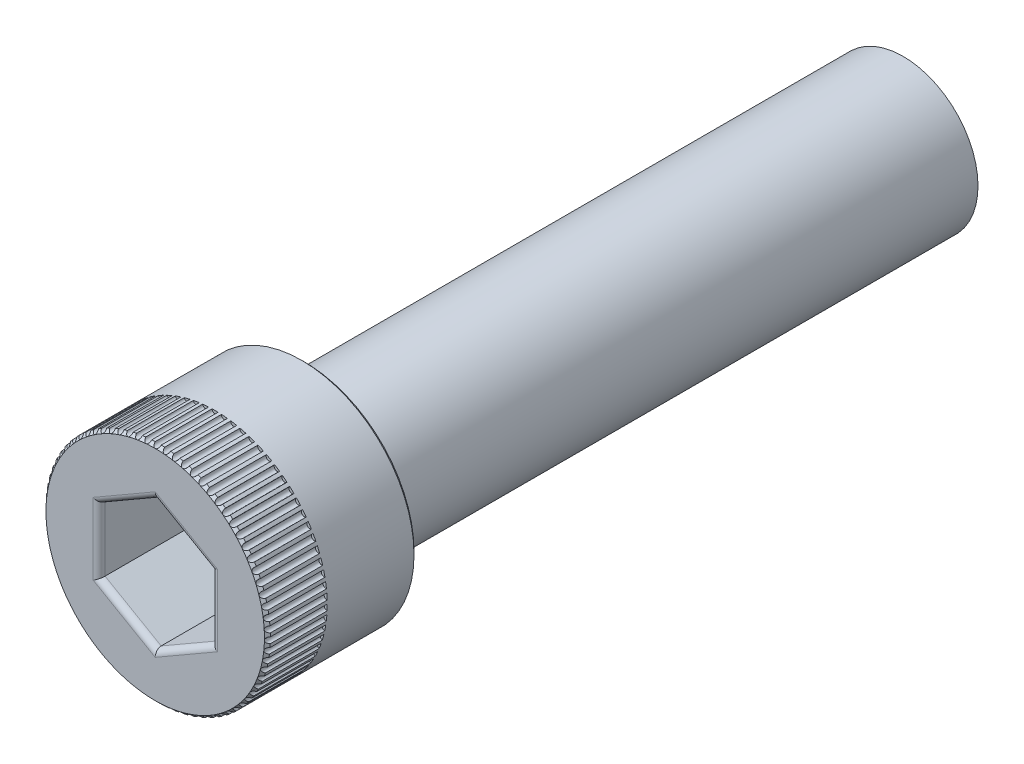
SolidWorks part; units mm, degrees
material "Alloy Steel"
ref_plane "Front Plane" through (0, 0, 0) normal (0, 0, 1) x (1, 0, 0)
ref_plane "Top Plane" through (0, 0, 0) normal (0, 1, 0) x (1, 0, 0)
ref_plane "Right Plane" through (0, 0, 0) normal (1, 0, 0) x (0, 0, -1)
sketch "Sketch1" plane through (0, 0, 0) normal (0, 0, 1) x (1, 0, 0)
  circle A0 centre (0, 0) radius 3.175
  dimension "D1" = 6.35
extrude "Extrude1" add sketch "Sketch1" along normal blind 25.4
sketch "Sketch2" plane through (0, 0, 25.4) normal (0, 0, 1) x (1, 0, 0)
  circle A0 centre (0, 0) radius 4.7625
  dimension "D1" = 9.525
extrude "Extrude2" add sketch "Sketch2" along normal blind 6.35
chamfer "Chamfer1" distance 0.127 angle 45 2 edges at (4.7625, 0, 25.4) (4.7625, 0, 31.75)
sketch "Sketch3" plane through (0, 0, 31.75) normal (0, 0, 1) x (1, 0, 0)
  line L1 (0, 2.7496) -> (-2.3813, 1.3748)
  line L2 (-2.3813, 1.3748) -> (-2.3813, -1.3748)
  line L3 (-2.3813, -1.3748) -> (0, -2.7496)
  line L4 (0, -2.7496) -> (2.3812, -1.3748)
  line L5 (2.3812, -1.3748) -> (2.3812, 1.3748)
  line L6 (2.3812, 1.3748) -> (0, 2.7496)
  circle A0 centre (0, 0) radius 2.3813 construction
  dimension "D1" = 4.7625
extrude "Cut-Extrude1" cut sketch "Sketch3" against normal blind 3.81
fillet "Fillet1" radius 0.254 6 edges at (1.1906, 2.0622, 31.75) (2.3812, 0, 31.75) (1.1906, -2.0622, 31.75) (-1.1906, -2.0622, 31.75) (-2.3813, 0, 31.75) (-1.1906, 2.0622, 31.75)
sketch "Sketch4" plane through (0, 0, 31.75) normal (0, 0, 1) x (1, 0, 0)
  circle A0 centre (0, 4.7625) radius 0.127
  circle A1 centre (0, 0) radius 4.7625 construction
  dimension "D1" = 0.254
extrude "Cut-Extrude2" cut sketch "Sketch4" against normal blind 2.54
pattern_circular "CirPattern1" count 75 over 360 about axis through (0, 0, 0) along (0, 0, 1) of "Cut-Extrude2"
